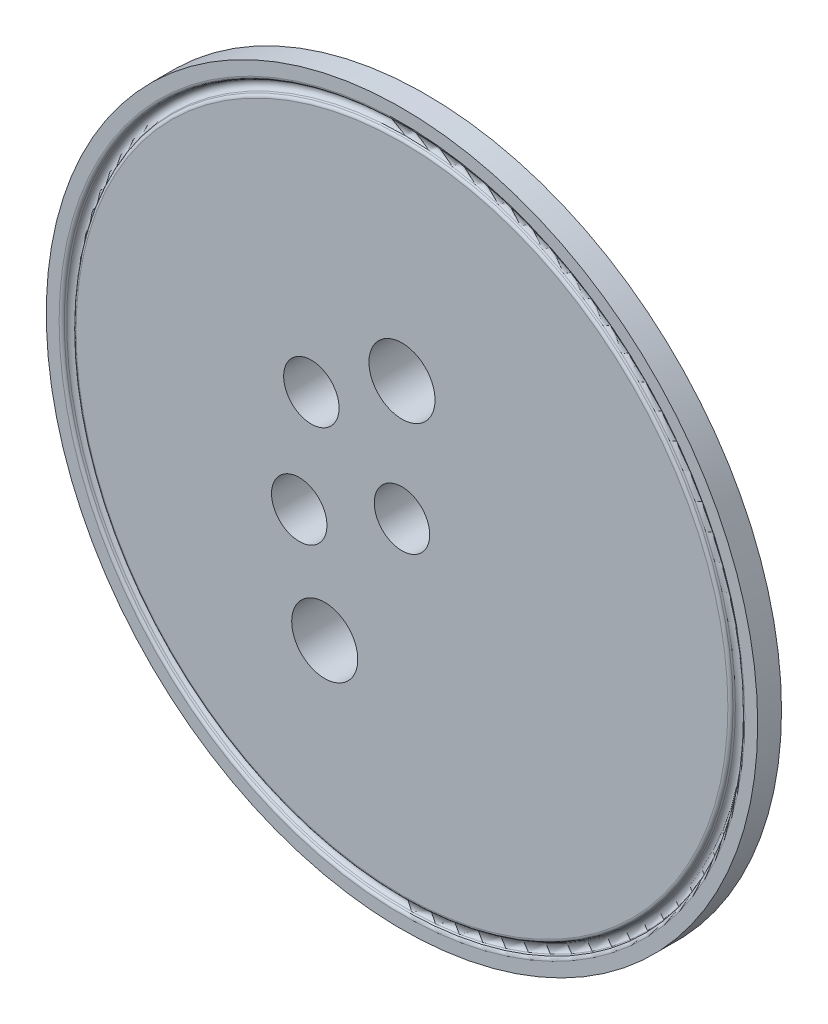
SolidWorks part; units mm, degrees
other "Markup1"
sketch "Sketch3"
ref_plane "Front Plane" through (0, 0, 0) normal (0, 0, 1) x (1, 0, 0)
ref_plane "Top Plane" through (0, 0, 0) normal (0, 1, 0) x (1, 0, 0)
ref_plane "Right Plane" through (0, 0, 0) normal (1, 0, 0) x (0, 0, -1)
sketch "Sketch1" plane through (0, 0, 0) normal (1, 0, 0) x (0, 0, -1)
  line L0 (0, 0) -> (11.0998, 0) construction
  line L1 (0, 0) -> (0, 76.4446)
  line L2 (0, 83.439) -> (5.588, 83.439)
  line L3 (5.588, 83.439) -> (11.0998, 68.2955)
  line L4 (11.0998, 68.2955) -> (11.0998, 0)
  line L5 (0, 80.4258) -> (0, 83.439)
  line L6 (0.4797, 79.701) -> (0.8729, 79.5341)
  line L7 (0.4797, 77.1694) -> (0.8729, 77.3363)
  line L8 (0, 79.9046) -> (0, 76.9658) construction
  line L9 (0, 78.4352) -> (0.4064, 78.4352) construction
  line L10 (0, 0) -> (11.0998, 0)
  arc A0 (0.8729, 77.3363) -> (0.8729, 79.5341) centre (0.4064, 78.4352) ccw
  arc A2 (0, 76.4446) -> (0.4797, 77.1694) centre (0.7874, 76.4446) cw
  arc A3 (0, 80.4258) -> (0.4797, 79.701) centre (0.7874, 80.4258) ccw
  dimension "K" = 1.1938
  dimension "L" = 0.7874
  dimension "I" = 20
  dimension "C" = 136.5909
  dimension "F" = 5.588
  dimension "H" = 0.4064
  dimension "B" = 156.8704
  dimension "A" = 166.878
  dimension "M" = 46
  dimension "N" = 23
  dimension "Length" = 11.0998
revolve "Revolve1" add sketch "Sketch1" angle 360 about L0
sketch "Sketch2" plane through (0, 0, -11.0998) normal (0, 0, -1) x (-1, 0, 0)
  circle A0 centre (0, 0) radius 6.5
  circle A1 centre (0, 0) radius 10.5 construction
  circle A4 centre (0, 27.9766) radius 7.75
  circle A10 centre (24.099, -10.1576) radius 6.5
  circle A11 centre (24.099, -10.1576) radius 10.5 construction
  circle A14 centre (21.2594, 15.1001) radius 6.5
  circle A15 centre (21.2594, 15.1001) radius 10.5 construction
  circle A16 centre (0, 27.9766) radius 10.5 construction
  circle A21 centre (18.1208, -33.7713) radius 7.75
  circle A22 centre (18.1208, -33.7713) radius 10.5 construction
  dimension "D3" = 15.5
  dimension "D14" = 21
extrude "Cut-Extrude1" cut sketch "Sketch2" against normal through all
